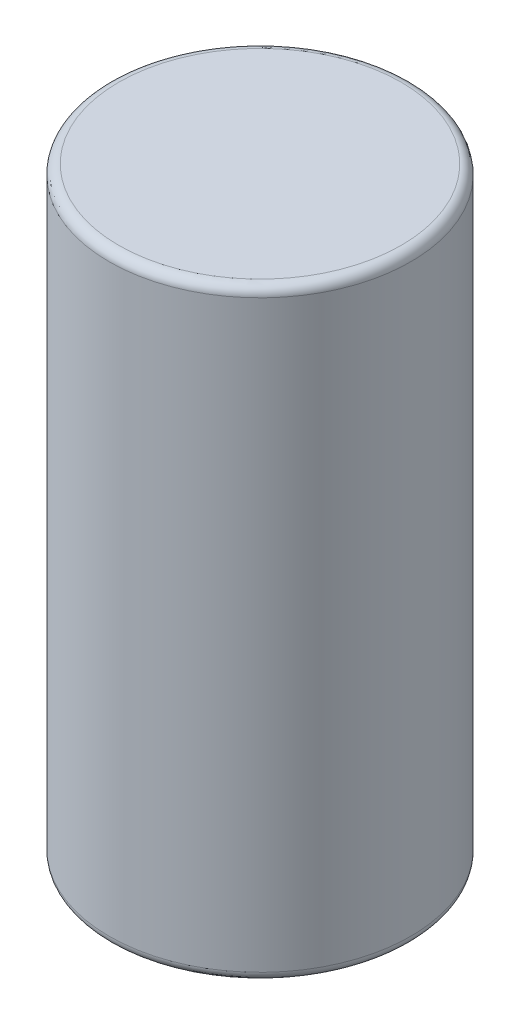
SolidWorks part; units mm, degrees
ref_plane "Front Plane" through (0, 0, 0) normal (0, 0, 1) x (1, 0, 0)
ref_plane "Top Plane" through (0, 0, 0) normal (0, 1, 0) x (1, 0, 0)
ref_plane "Right Plane" through (0, 0, 0) normal (1, 0, 0) x (0, 0, -1)
sketch "Sketch1" plane through (0, 0, 0) normal (0, 0, 1) x (1, 0, 0)
  line L0 (0, 0) -> (0, 12.7) construction
  line L1 (0, 12.7) -> (3.175, 12.7)
  line L2 (3.175, 12.7) -> (3.175, 0)
  line L3 (3.175, 0) -> (0, 0)
  line L4 (0, 12.7) -> (0, 0)
  dimension "D1" = 12.7
  dimension "D2" = 6.35
revolve "Revolve1" add sketch "Sketch1" angle 360 about L0
fillet "Fillet1" radius 0.2 2 edges at (0, 0, -3.175) (0, 12.7, -3.175)
